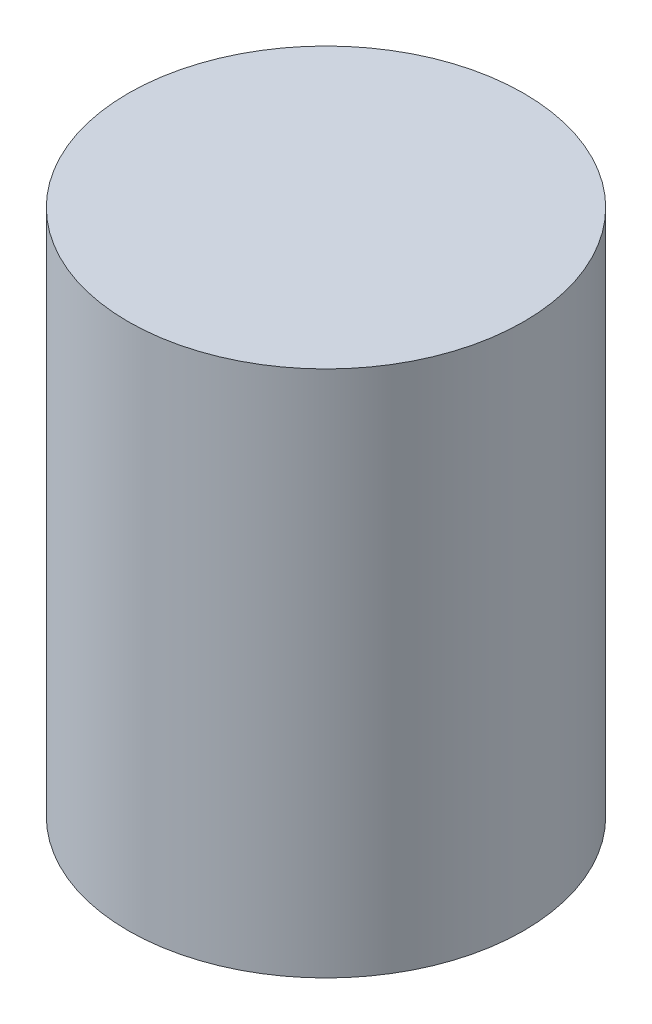
SolidWorks part; units mm, degrees
ref_plane "Спереди" through (0, 0, 0) normal (0, 0, 1) x (1, 0, 0)
ref_plane "Сверху" through (0, 0, 0) normal (0, 1, 0) x (1, 0, 0)
ref_plane "Справа" through (0, 0, 0) normal (1, 0, 0) x (0, 0, -1)
sketch "Sketch1" plane through (0, 0, 0) normal (0, 1, 0) x (1, 0, 0)
  circle A0 centre (0, 0) radius 7.5
  dimension "D1" = 15
extrude "Boss-Extrude1" add sketch "Sketch1" along normal blind 20
sketch "Sketch2" plane through (0, 0, 0) normal (0, -1, 0) x (1, 0, 0)
  circle A0 centre (0, 0) radius 5
  dimension "D1" = 10
extrude "Cut-Extrude1" cut sketch "Sketch2" against normal blind 4
sketch "Sketch3" plane through (0, 4, 0) normal (0, -1, 0) x (1, 0, 0)
  line L0 (-1.7321, -2.571) -> (3.0483, -0.5639)
  line L1 (0.6581, -1.5674) -> (-1.2001, 2.8583) construction
  circle A0 centre (0, 0) radius 3.1 construction
  arc A1 (-1.7321, -2.571) -> (3.0483, -0.5639) centre (0, 0) cw
  dimension "D1" = 6.2
  dimension "D2" = 4.8
extrude "Cut-Extrude2" cut sketch "Sketch3" against normal blind 12
chamfer "Chamfer1" distance 1 angle 30 1 edges at (0, 0, -5)
